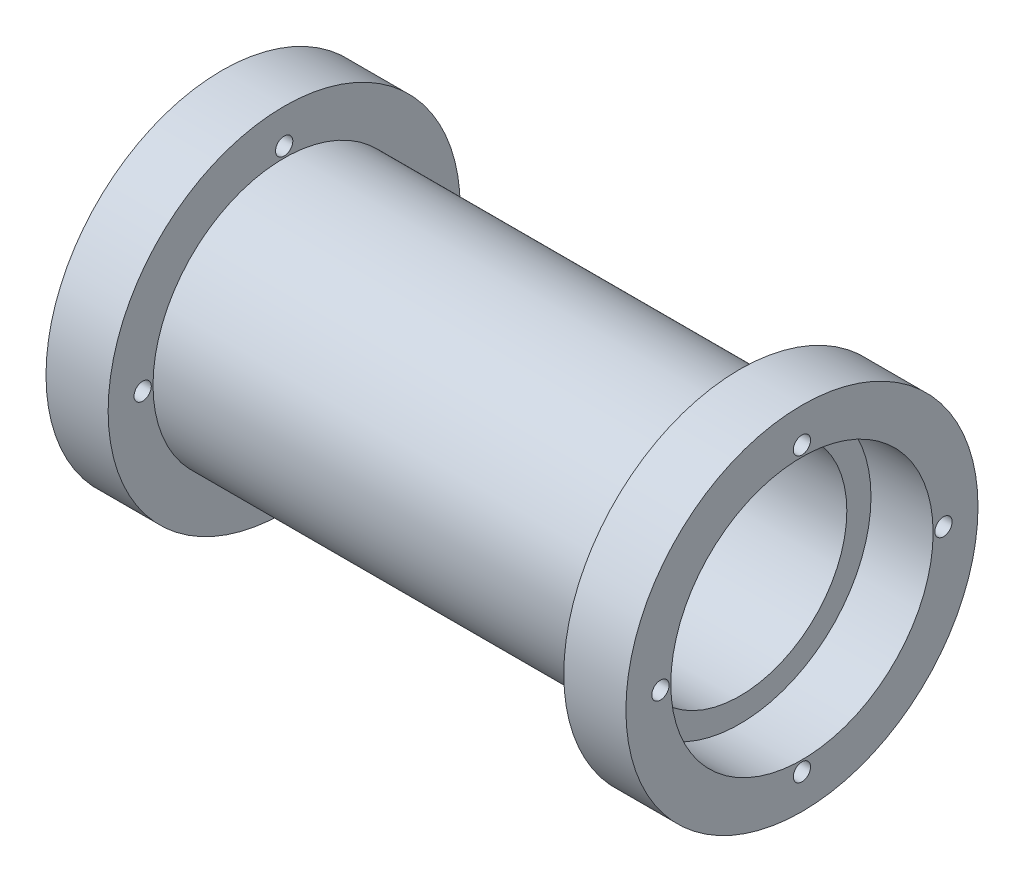
SolidWorks part; units mm, degrees
ref_plane "前视基准面" through (0, 0, 0) normal (0, 0, 1) x (1, 0, 0)
ref_plane "上视基准面" through (0, 0, 0) normal (0, 1, 0) x (1, 0, 0)
ref_plane "右视基准面" through (0, 0, 0) normal (1, 0, 0) x (0, 0, -1)
sketch "草图1" plane through (0, 0, 0) normal (1, 0, 0) x (0, 0, -1)
  circle A0 centre (0, 0) radius 31
  circle A1 centre (0, 0) radius 51
extrude "凸台-拉伸1" add sketch "草图1" along normal blind 18
sketch "草图2" plane through (18, 0, 0) normal (1, 0, 0) x (0, 0, -1)
  circle A0 centre (0, 0) radius 31
  circle A1 centre (0, 0) radius 38
extrude "凸台-拉伸2" add sketch "草图2" along normal blind 132
sketch "草图3" plane through (150, 0, 0) normal (1, 0, 0) x (0, 0, -1)
  circle A0 centre (0, 0) radius 38
  circle A1 centre (0, 0) radius 51
extrude "凸台-拉伸3" add sketch "草图3" along normal blind 18 separate body
sketch "草图4" plane through (0, 0, 0) normal (-1, 0, 0) x (0, 0, 1)
  line L0 (0, 0) -> (60.5842, 0) construction
  line L1 (60.5842, 0) -> (-61.6406, 0) construction
  line L2 (0, 0) -> (0, 71.2022) construction
  line L3 (0, 71.2022) -> (0, -60.4245) construction
  circle A0 centre (0, 41) radius 2.5
  circle A1 centre (41, 0) radius 2.5
  circle A2 centre (0, -41) radius 2.5
  circle A3 centre (-41, 0) radius 2.5
  point P17 (0, 0)
  dimension "D1" = 4
extrude "切除-拉伸1" cut sketch "草图4" against normal up to surface (168 mm away)
